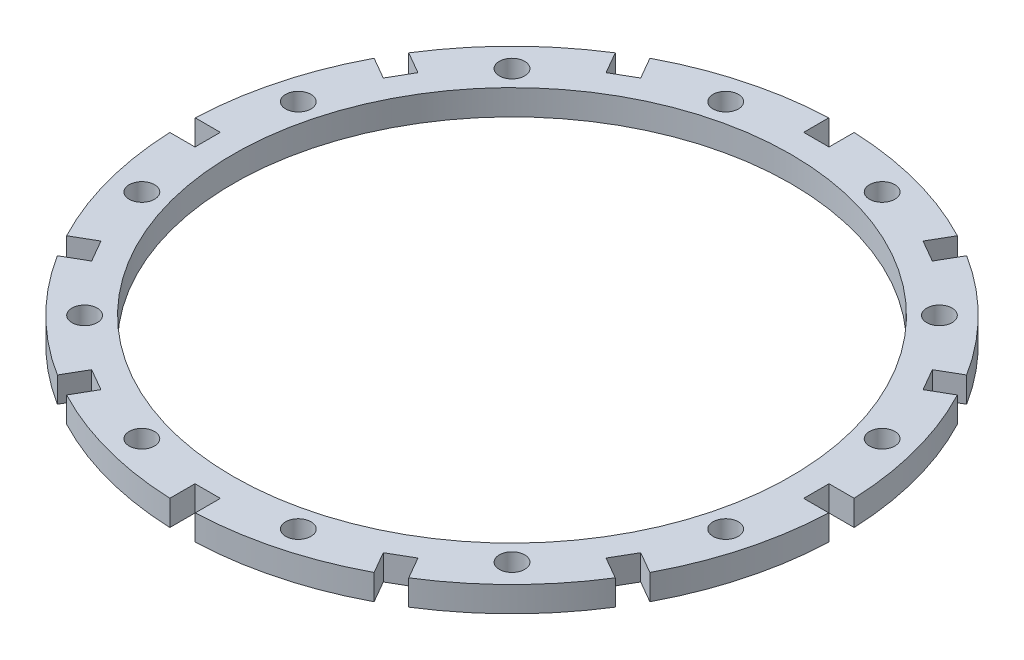
SolidWorks part; units mm, degrees
ref_plane "Front Plane" through (0, 0, 0) normal (0, 0, 1) x (1, 0, 0)
ref_plane "Top Plane" through (0, 0, 0) normal (0, 1, 0) x (1, 0, 0)
ref_plane "Right Plane" through (0, 0, 0) normal (1, 0, 0) x (0, 0, -1)
sketch "Sketch1" plane through (0, 0, 0) normal (0, 1, 0) x (1, 0, 0)
  circle A1 centre (0, 0) radius 119.99
  circle A2 centre (0, 0) radius 141.81
  dimension "D2" = 239.98
  dimension "D3" = 283.62
extrude "Boss-Extrude1" add sketch "Sketch1" along normal blind 10.91
sketch "Sketch2" plane through (0, 10.91, 0) normal (0, 1, 0) x (1, 0, 0)
  line L0 (-71.6358, -134.9869) -> (-60.7258, -116.0902)
  line L1 (5.455, -152.72) -> (-5.455, -152.72)
  line L2 (5.455, -152.72) -> (5.455, -130.9)
  line L3 (5.455, -130.9) -> (-5.455, -130.9)
  line L4 (-5.455, -152.72) -> (-5.455, -130.9)
  line L5 (5.455, -152.72) -> (-5.455, -130.9) construction
  line L6 (5.455, -130.9) -> (-5.455, -152.72) construction
  line L7 (-71.6358, -134.9869) -> (-81.0842, -129.5319)
  line L8 (-81.0842, -129.5319) -> (-70.1742, -110.6352)
  line L9 (-60.7258, -116.0902) -> (-70.1742, -110.6352)
  line L10 (-129.5319, -81.0842) -> (-110.6352, -70.1742)
  line L11 (-129.5319, -81.0842) -> (-134.9869, -71.6358)
  line L12 (-134.9869, -71.6358) -> (-116.0902, -60.7258)
  line L13 (-110.6352, -70.1742) -> (-116.0902, -60.7258)
  line L14 (-152.72, -5.455) -> (-130.9, -5.455)
  line L15 (-152.72, -5.455) -> (-152.72, 5.455)
  line L16 (-152.72, 5.455) -> (-130.9, 5.455)
  line L17 (-130.9, -5.455) -> (-130.9, 5.455)
  line L18 (-134.9869, 71.6358) -> (-116.0902, 60.7258)
  line L19 (-134.9869, 71.6358) -> (-129.5319, 81.0842)
  line L20 (-129.5319, 81.0842) -> (-110.6352, 70.1742)
  line L21 (-116.0902, 60.7258) -> (-110.6352, 70.1742)
  line L22 (-81.0842, 129.5319) -> (-70.1742, 110.6352)
  line L23 (-81.0842, 129.5319) -> (-71.6358, 134.9869)
  line L24 (-71.6358, 134.9869) -> (-60.7258, 116.0902)
  line L25 (-70.1742, 110.6352) -> (-60.7258, 116.0902)
  line L26 (-5.455, 152.72) -> (-5.455, 130.9)
  line L27 (-5.455, 152.72) -> (5.455, 152.72)
  line L28 (5.455, 152.72) -> (5.455, 130.9)
  line L29 (-5.455, 130.9) -> (5.455, 130.9)
  line L30 (71.6358, 134.9869) -> (60.7258, 116.0902)
  line L31 (71.6358, 134.9869) -> (81.0842, 129.5319)
  line L32 (81.0842, 129.5319) -> (70.1742, 110.6352)
  line L33 (60.7258, 116.0902) -> (70.1742, 110.6352)
  line L34 (129.5319, 81.0842) -> (110.6352, 70.1742)
  line L35 (129.5319, 81.0842) -> (134.9869, 71.6358)
  line L36 (134.9869, 71.6358) -> (116.0902, 60.7258)
  line L37 (110.6352, 70.1742) -> (116.0902, 60.7258)
  line L38 (152.72, 5.455) -> (130.9, 5.455)
  line L39 (152.72, 5.455) -> (152.72, -5.455)
  line L40 (152.72, -5.455) -> (130.9, -5.455)
  line L41 (130.9, 5.455) -> (130.9, -5.455)
  line L42 (134.9869, -71.6358) -> (116.0902, -60.7258)
  line L43 (134.9869, -71.6358) -> (129.5319, -81.0842)
  line L44 (129.5319, -81.0842) -> (110.6352, -70.1742)
  line L45 (116.0902, -60.7258) -> (110.6352, -70.1742)
  line L46 (81.0842, -129.5319) -> (70.1742, -110.6352)
  line L47 (81.0842, -129.5319) -> (71.6358, -134.9869)
  line L48 (71.6358, -134.9869) -> (60.7258, -116.0902)
  line L49 (70.1742, -110.6352) -> (60.7258, -116.0902)
  circle A0 centre (0, 0) radius 141.81
  circle A1 centre (0, 0) radius 130.9
  point P4 (0, -141.81)
  circle M7 centre (0, 0) radius 141.81
  dimension "D1" = 261.8
  dimension "D2" = 283.62
  dimension "D3" = 10.91
  dimension "D4" = 130.9
  dimension "D5" = 12
extrude "Cut-Extrude1" cut sketch "Sketch2" against normal blind 10.91 contours L4 L2 L3 M7 | L0 L9 L8 L7 | L10 L13 L12 L11 | L14 L17 L16 L15 | L18 L21 L20 L19 | L22 L25 L24 L23 | L26 L29 L28 L27 | L30 L33 L32 L31 | L34 L37 L36 L35 | L38 L41 L40 L39 | L42 L45 L44 L43 | L46 L49 L48 L47
sketch "Sketch3" plane through (0, 10.91, 0) normal (0, 1, 0) x (1, 0, 0)
  line L0 (0, 0) -> (-33.6467, -125.571)
  line L1 (-5.455, -141.705) -> (-5.455, -130.9) construction
  circle A12 centre (-33.6467, -125.571) radius 5.455
  circle A13 centre (-91.9244, -91.9244) radius 5.455
  circle A14 centre (-125.571, -33.6467) radius 5.455
  circle A15 centre (-125.571, 33.6467) radius 5.455
  circle A16 centre (-91.9244, 91.9244) radius 5.455
  circle A17 centre (-33.6467, 125.571) radius 5.455
  circle A18 centre (33.6467, 125.571) radius 5.455
  circle A19 centre (91.9244, 91.9244) radius 5.455
  circle A20 centre (125.571, 33.6467) radius 5.455
  circle A21 centre (125.571, -33.6467) radius 5.455
  circle A22 centre (91.9244, -91.9244) radius 5.455
  circle A23 centre (33.6467, -125.571) radius 5.455
  point P4 (0, 0)
  point P5 (0, 0)
  dimension "D2" = 15
  dimension "D1" = 10.91
  dimension "D3" = 12
extrude "Cut-Extrude2" cut sketch "Sketch3" against normal blind 10.91
